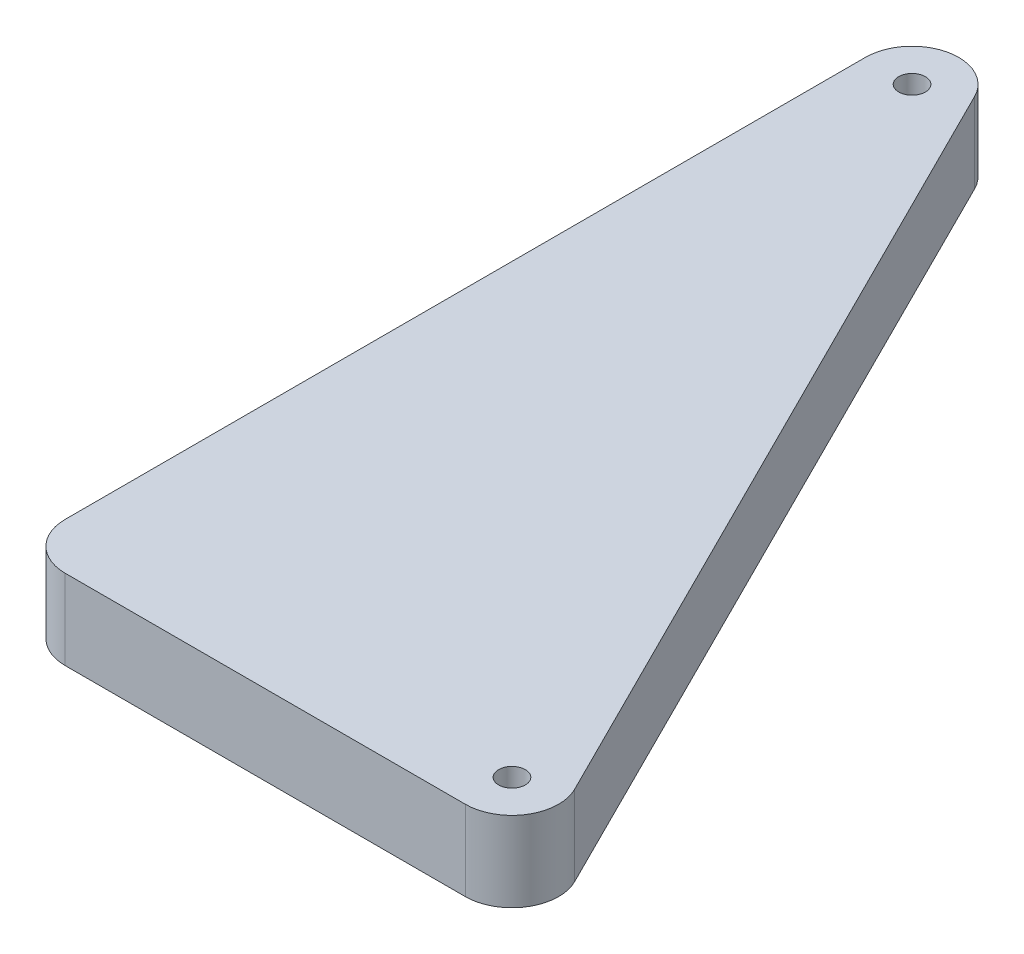
SolidWorks part; units mm, degrees
ref_plane "Front Plane" through (0, 0, 0) normal (0, 0, 1) x (1, 0, 0)
ref_plane "Top Plane" through (0, 0, 0) normal (0, 1, 0) x (1, 0, 0)
ref_plane "Right Plane" through (0, 0, 0) normal (1, 0, 0) x (0, 0, -1)
sketch "Sketch1" plane through (0, 0, 0) normal (0, 1, 0) x (1, 0, 0)
  line L0 (30, -63.5) -> (0, -63.5)
  line L1 (-3.5, -60) -> (-3.5, 0)
  line L2 (3.1305, 1.5652) -> (33.1305, -58.4348)
  circle A0 centre (0, 0) radius 1
  circle A1 centre (30, -60) radius 1
  arc A2 (30, -63.5) -> (33.1305, -58.4348) centre (30, -60) ccw
  arc A3 (3.1305, 1.5652) -> (-3.5, 0) centre (0, 0) ccw
  arc A4 (-3.5, -60) -> (0, -63.5) centre (0, -60) ccw
  dimension "D3" = 2
  dimension "D4" = 3.5
  dimension "D1" = 60
  dimension "D2" = 30
extrude "Boss-Extrude1" add sketch "Sketch1" along normal blind 6
